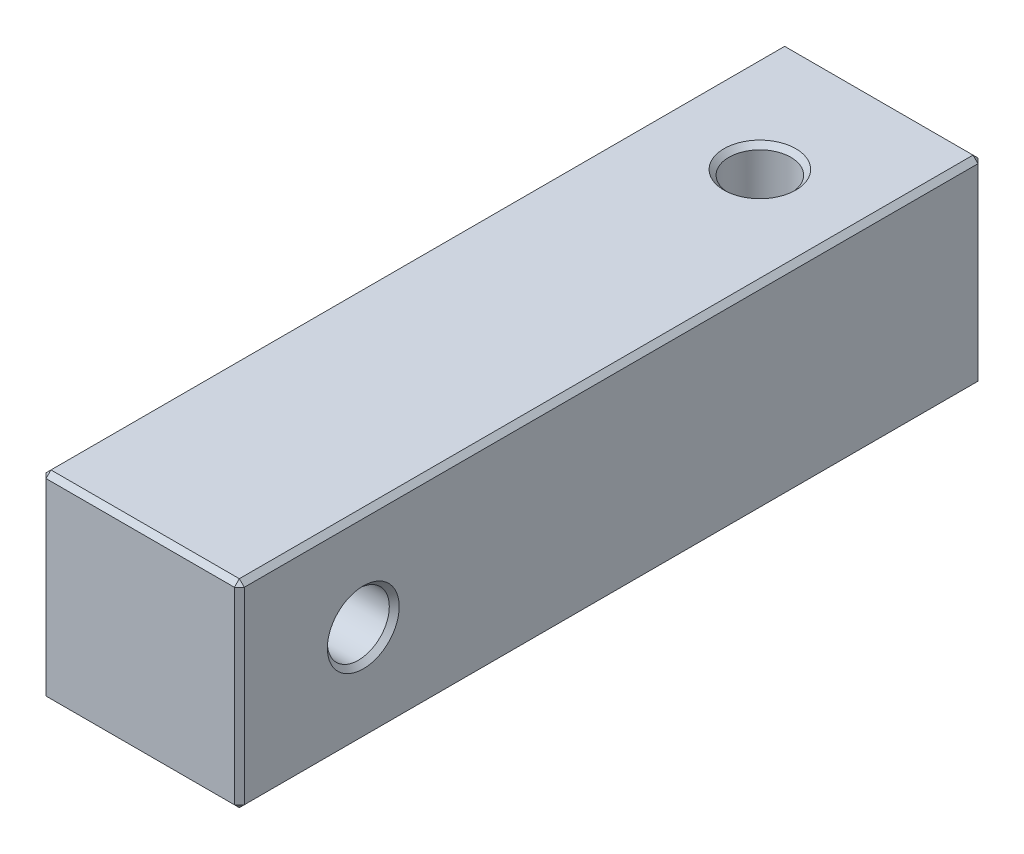
SolidWorks part; units mm, degrees
ref_plane "前视基准面" through (0, 0, 0) normal (0, 0, 1) x (1, 0, 0)
ref_plane "上视基准面" through (0, 0, 0) normal (0, 1, 0) x (1, 0, 0)
ref_plane "右视基准面" through (0, 0, 0) normal (1, 0, 0) x (0, 0, -1)
sketch "草图1" plane through (0, 0, 0) normal (0, 0, 1) x (1, 0, 0)
  line L1 (-4, 4) -> (4, 4)
  line L2 (-4, 4) -> (-4, -4)
  line L3 (-4, -4) -> (4, -4)
  line L4 (4, 4) -> (4, -4)
  line L5 (-4, 4) -> (4, -4) construction
  line L6 (-4, -4) -> (4, 4) construction
  point P0 (0, 0)
  dimension "D1" = 8
extrude "凸台-拉伸1" add sketch "草图1" along normal mid plane 30
hole_wizard "M3 螺纹孔1" positions "草图2" profile "草图3" tap size "M3" standard "GB" end condition through all
sketch "草图2" plane through (4, 0, 0) normal (1, 0, 0) x (0, 0, -1)
  line L0 (0, 0) -> (50000, 0) construction
  line L1 (15, -4) -> (15, 4) construction
  point P0 (-10, 0)
  point P7 (0, 0)
  dimension "D1" = 25
sketch "草图3" plane through (4, 0, 10) normal (0, 1, 0) x (0, 0, -1)
  line L0 (0, 0) -> (0, 8)
  line L1 (0, 8) -> (1.25, 8)
  line L2 (1.25, 8) -> (1.25, 0)
  line L5 (1.25, 0) -> (0, 0)
  line L11 (0, -6.35) -> (0, 107.95) construction
  dimension "通孔螺纹孔钻头直径" = 2.5
  dimension "通孔螺纹孔钻头深度" = 8
cosmetic thread "孔螺蚊线1"
hole_wizard "M3 螺纹孔2" positions "草图4" profile "草图5" tap size "M3" standard "GB" end condition through all
sketch "草图4" plane through (0, 4, 0) normal (0, 1, 0) x (1, 0, 0)
  line L0 (4, -15) -> (-4, -15) construction
  line L1 (0, 0) -> (0, 50000) construction
  point P0 (0, 10)
  point P8 (0, 0)
  dimension "D1" = 25
sketch "草图5" plane through (0, 4, -10) normal (1, 0, 0) x (0, 0, 1)
  line L0 (0, 0) -> (0, 8)
  line L1 (0, 8) -> (1.25, 8)
  line L2 (1.25, 8) -> (1.25, 0)
  line L5 (1.25, 0) -> (0, 0)
  line L11 (0, -6.35) -> (0, 107.95) construction
  dimension "通孔螺纹孔钻头直径" = 2.5
  dimension "通孔螺纹孔钻头深度" = 8
cosmetic thread "孔螺蚊线2"
chamfer "倒角1" distance 0.2 angle 45 16 edges at (0, -4, -8.75) (-4, 0, 8.75) (0, 4, -8.75) (0, -4, 15) (0, -4, -15) (-4, 0, 15) (-4, -4, 0) (-4, 0, -15) (0, 4, 15) (-4, 4, 0) (0, 4, -15) (4, -4, 0) (4, 0, 15) (4, 4, 0) (4, 0, -15) (4, 0, 8.75)
